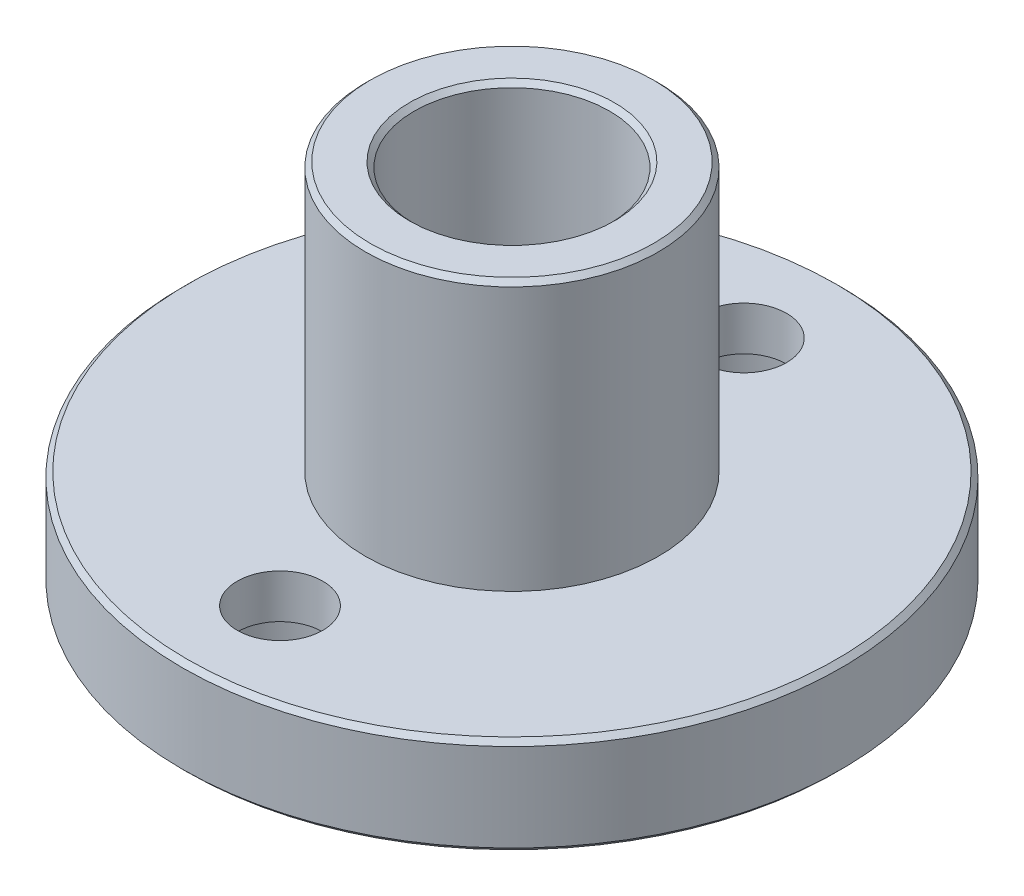
SolidWorks part; units mm, degrees
ref_plane "Front Plane" through (0, 0, 0) normal (0, 0, 1) x (1, 0, 0)
ref_plane "Top Plane" through (0, 0, 0) normal (0, 1, 0) x (1, 0, 0)
ref_plane "Right Plane" through (0, 0, 0) normal (1, 0, 0) x (0, 0, -1)
other "Configuration Table"
sketch "草图1" plane through (0, 0, 0) normal (0, 1, 0) x (1, 0, 0)
  circle A1 centre (0, 0) radius 13.5
extrude "凸台-拉伸1" add sketch "草图1" along normal blind 4
sketch "草图2" plane through (0, 4, 0) normal (0, 1, 0) x (1, 0, 0)
  circle A0 centre (0, 0) radius 6
extrude "凸台-拉伸2" add sketch "草图2" along normal blind 11
sketch "草图3" plane through (0, 0, 0) normal (0, -1, 0) x (-1, 0, 0)
  circle A0 centre (0, 0) radius 4
extrude "切除-拉伸1" cut sketch "草图3" against normal through all
sketch "草图4" plane through (0, 0, 0) normal (0, -1, 0) x (1, 0, 0)
  line L0 (0, 0) -> (0, 9.5) construction
  line L1 (0, 0) -> (0, -9.5) construction
  circle A1 centre (0, 9.5) radius 1.75
  circle A3 centre (0, -9.5) radius 1.75
extrude "切除-拉伸2" cut sketch "草图4" against normal through all
sketch "草图5" plane through (0, 0, 0) normal (0, -1, 0) x (-1, 0, 0)
  circle A0 centre (0, -9.5) radius 3
  circle A1 centre (0, 9.5) radius 3
extrude "切除-拉伸3" cut sketch "草图5" against normal blind 2.2
chamfer "倒角1" distance 0.2 angle 45 4 edges at (0, 15, -4) (0, 15, 6) (0, 4, 13.5) (0, 0, 13.5)
